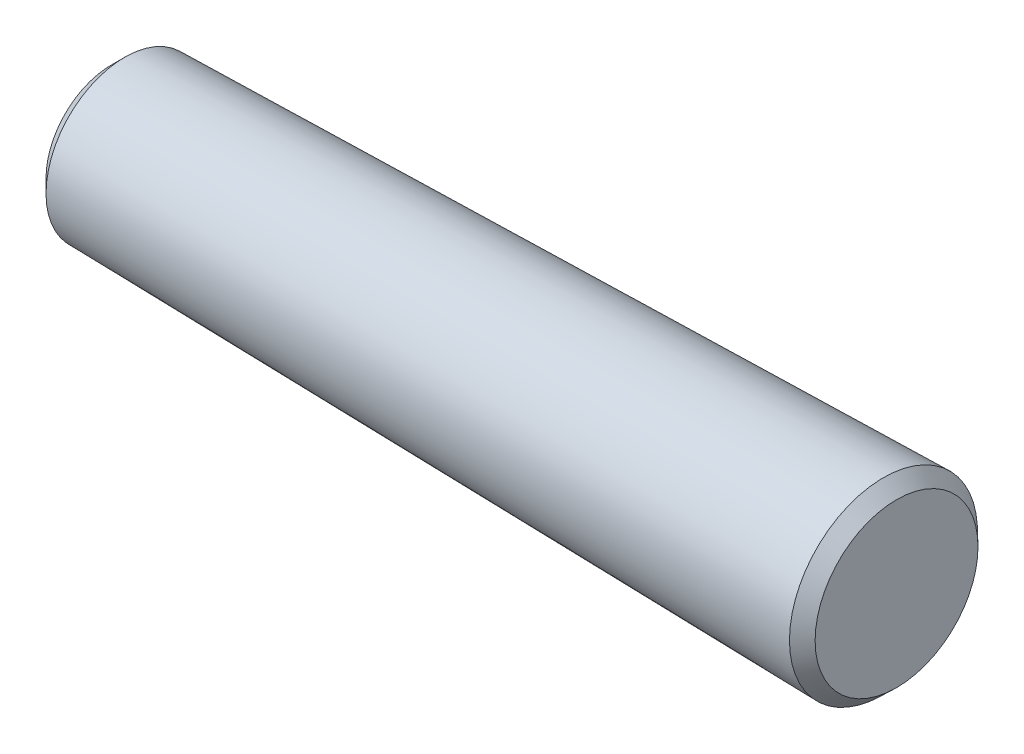
SolidWorks part; units mm, degrees
ref_plane "前视基准面" through (0, 0, 0) normal (0, 0, 1) x (1, 0, 0)
ref_plane "上视基准面" through (0, 0, 0) normal (0, 1, 0) x (1, 0, 0)
ref_plane "右视基准面" through (0, 0, 0) normal (1, 0, 0) x (0, 0, -1)
other "Configuration Table"
sketch "草图1" plane through (0, 0, 0) normal (0, 0, 1) x (1, 0, 0)
  line L0 (0, 0) -> (125.7769, 0) construction
  line L1 (0, 0) -> (0, 3)
  line L2 (0, 3) -> (30, 3)
  line L3 (30, 3) -> (30, 0)
  line L4 (30, 0) -> (0, 0)
  dimension "D1" = 30
  dimension "D2" = 3
revolve "旋转1" add sketch "草图1" angle 360 about L4
draft "拔模1" type of draft neutral plane draft angle 1.15 faces to draft 1 face at (0, 0, -3) neutral plane through (0, 0, 0) neutral plane normal (-1, 0, 0) parameters "D1"=1.15
chamfer "倒角1" distance 0.5 angle 45 2 edges at (0, 0, -3) (30, 0, -3.6022)
